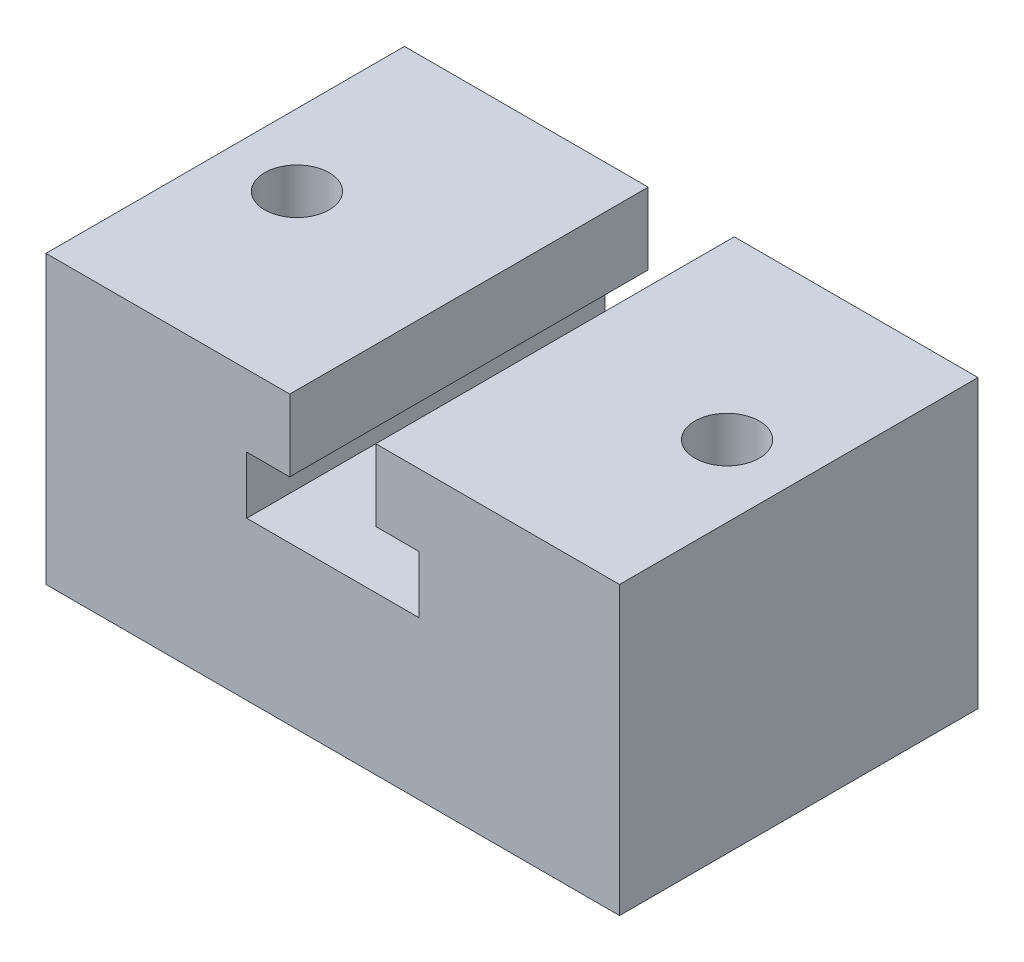
SolidWorks part; units mm, degrees
ref_plane "前视基准面" through (0, 0, 0) normal (0, 0, 1) x (1, 0, 0)
ref_plane "上视基准面" through (0, 0, 0) normal (0, 1, 0) x (1, 0, 0)
ref_plane "右视基准面" through (0, 0, 0) normal (1, 0, 0) x (0, 0, -1)
ref_plane "基准面1" through (0, 0, -25) normal (0, 0, 1) x (1, 0, 0)
sketch "草图1" plane through (0, 0, -25) normal (0, 0, 1) x (1, 0, 0)
  line L0 (-40, 0) -> (40, 0)
  line L1 (40, 0) -> (40, 40)
  line L2 (40, 40) -> (-40, 40)
  line L3 (-40, 40) -> (-40, 0)
extrude "凸台-拉伸1" add sketch "草图1" along normal blind 50
sketch "草图2" plane through (0, 0, -25) normal (0, 0, 1) x (1, 0, 0)
  line L0 (-6, 40) -> (6, 40)
  line L1 (6, 40) -> (6, 30)
  line L2 (6, 30) -> (12, 30)
  line L3 (12, 30) -> (12, 22)
  line L4 (12, 22) -> (-12, 22)
  line L5 (-12, 22) -> (-12, 30)
  line L6 (-12, 30) -> (-6, 30)
  line L7 (-6, 30) -> (-6, 40)
extrude "切除-拉伸1" cut sketch "草图2" along normal through all
ref_plane "基准面2" through (0, 40, 0) normal (0, 1, 0) x (1, 0, 0)
sketch "草图3" plane through (0, 40, 0) normal (0, 1, 0) x (1, 0, 0)
  circle A0 centre (-30, 0) radius 4.5
  circle A1 centre (30, 0) radius 4.5
extrude "切除-拉伸2" cut sketch "草图3" against normal through all
